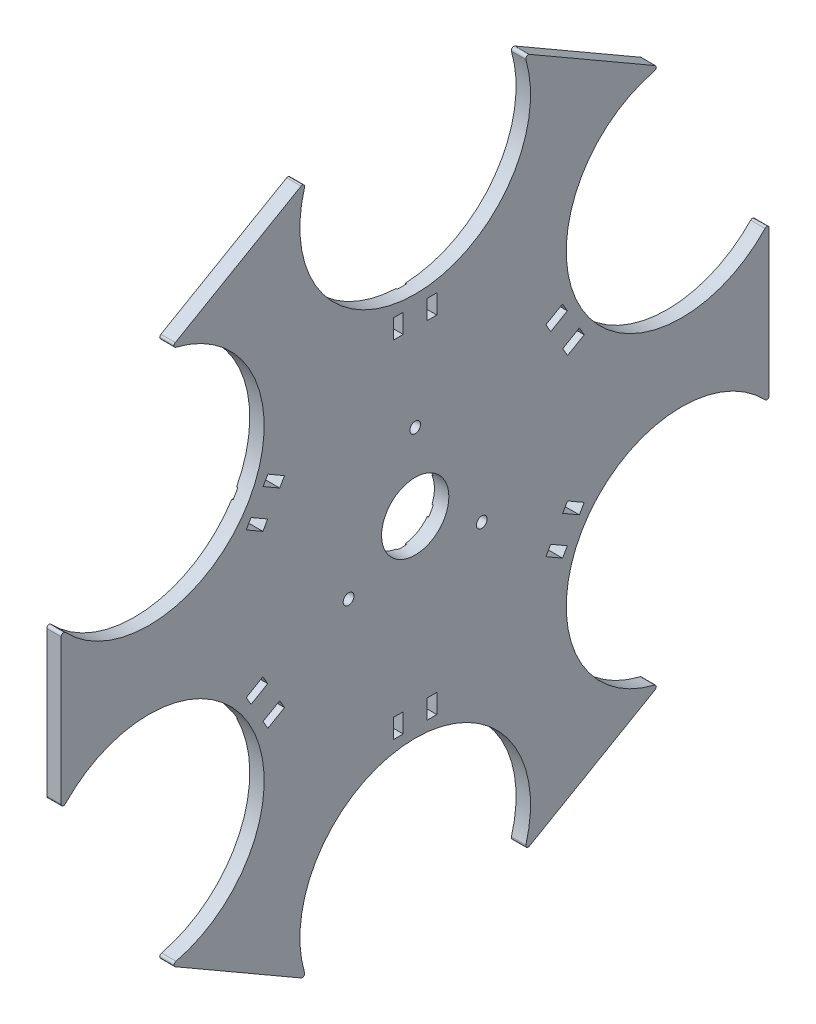
SolidWorks part; units mm, degrees
ref_plane "Front Plane" through (0, 0, 0) normal (0, 0, 1) x (1, 0, 0)
ref_plane "Top Plane" through (0, 0, 0) normal (0, 1, 0) x (1, 0, 0)
ref_plane "Right Plane" through (0, 0, 0) normal (1, 0, 0) x (0, 0, -1)
sketch "Sketch2" plane through (0, 0, 0) normal (1, 0, 0) x (0, 0, -1)
  line L0 (35.921, 114.3) -> (-35.921, 114.3) construction
  line L1 (81.0262, 88.2585) -> (35.921, 114.3)
  line L2 (116.9472, -26.0415) -> (116.9472, 26.0415)
  line L3 (35.921, -114.3) -> (81.0262, -88.2585)
  line L4 (-81.0262, -88.2585) -> (-35.921, -114.3)
  line L5 (-116.9472, 26.0415) -> (-116.9472, -26.0415)
  line L6 (-35.921, 114.3) -> (-81.0262, 88.2585)
  circle A0 centre (0, 0) radius 101.6 construction
  arc A1 (-35.921, 114.3) -> (35.921, 114.3) centre (0, 101.6) ccw
  arc A2 (81.0262, 88.2585) -> (116.9472, 26.0415) centre (87.9882, 50.8) ccw
  arc A3 (116.9472, -26.0415) -> (81.0262, -88.2585) centre (87.9882, -50.8) ccw
  arc A4 (35.921, -114.3) -> (-35.921, -114.3) centre (0, -101.6) ccw
  arc A5 (-81.0262, -88.2585) -> (-116.9472, -26.0415) centre (-87.9882, -50.8) ccw
  arc A6 (-116.9472, 26.0415) -> (-81.0262, 88.2585) centre (-87.9882, 50.8) ccw
  circle A7 centre (0, 0) radius 11.11
  point P23 (0, 0)
  point P34 (0, 0)
  dimension "D1" = 203.2
  dimension "D2" = 114.3
  dimension "D3" = 76.2
  dimension "D4" = 6
  dimension "D5" = 6
extrude "Boss-Extrude1" add sketch "Sketch2" along normal blind 4.7625
sketch "Sketch3" plane through (0, 0, 0) normal (-1, 0, 0) x (0, 0, 1)
  line L0 (1.5875, 10.6044) -> (-1.5875, 10.6044)
  line L1 (1.5875, 192.5956) -> (-1.5875, 192.5956)
  line L2 (1.5875, 192.5956) -> (1.5875, 10.6044)
  line L3 (167.5864, 94.923) -> (165.9989, 97.6726)
  line L4 (-1.5875, 192.5956) -> (-1.5875, 10.6044)
  line L5 (1.5875, 192.5956) -> (-1.5875, 10.6044) construction
  line L6 (1.5875, 10.6044) -> (-1.5875, 192.5956) construction
  line L7 (167.5864, 94.923) -> (9.9774, 3.9274)
  line L8 (165.9989, 97.6726) -> (8.3899, 6.677)
  line L9 (9.9774, 3.9274) -> (8.3899, 6.677)
  line L10 (165.9989, -97.6726) -> (167.5864, -94.923)
  line L11 (165.9989, -97.6726) -> (8.3899, -6.677)
  line L12 (167.5864, -94.923) -> (9.9774, -3.9274)
  line L13 (8.3899, -6.677) -> (9.9774, -3.9274)
  line L14 (-1.5875, -192.5956) -> (1.5875, -192.5956)
  line L15 (-1.5875, -192.5956) -> (-1.5875, -10.6044)
  line L16 (1.5875, -192.5956) -> (1.5875, -10.6044)
  line L17 (-1.5875, -10.6044) -> (1.5875, -10.6044)
  line L18 (-167.5864, -94.923) -> (-165.9989, -97.6726)
  line L19 (-167.5864, -94.923) -> (-9.9774, -3.9274)
  line L20 (-165.9989, -97.6726) -> (-8.3899, -6.677)
  line L21 (-9.9774, -3.9274) -> (-8.3899, -6.677)
  line L22 (-165.9989, 97.6726) -> (-167.5864, 94.923)
  line L23 (-165.9989, 97.6726) -> (-8.3899, 6.677)
  line L24 (-167.5864, 94.923) -> (-9.9774, 3.9274)
  line L25 (-8.3899, 6.677) -> (-9.9774, 3.9274)
  point P0 (0, 101.6)
  point P28 (0, 0)
  point P29 (0, 0)
  dimension "D1" = 3.175
  dimension "D2" = 6
extrude "Cut-Extrude1" cut sketch "Sketch3" against normal blind 0.3969
fillet "Fillet1" radius 0.7937 12 edges at (2.3813, -114.3, 35.921) (2.3813, -114.3, -35.921) (2.3813, -88.2585, -81.0262) (2.3813, -26.0415, -116.9472) (2.3813, 88.2585, -81.0262) (2.3813, 26.0415, -116.9472) (2.3813, -88.2585, 81.0262) (2.3813, -26.0415, 116.9472) (2.3813, 26.0415, 116.9472) (2.3813, 88.2585, 81.0262) (2.3813, 114.3, -35.921) (2.3813, 114.3, 35.921)
hole_wizard "9/64 (0.14063) Diameter Hole1" positions "Sketch7" profile "Sketch6" hole size "9/64" standard "ANSI Inch" end condition through all
sketch "Sketch7" plane through (0, 0, 0) normal (-1, 0, 0) x (0, 0, 1)
  line L0 (0, 0) -> (0, 25.4) construction
  line L1 (0, 0) -> (21.997, -12.7) construction
  line L2 (0, 0) -> (-21.997, -12.7) construction
  circle A0 centre (0, 0) radius 25.4
  point P5 (0, 25.4)
  point P10 (21.997, -12.7)
  point P13 (-21.997, -12.7)
  dimension "D1" = 120
  dimension "D2" = 120
sketch "Sketch6" plane through (0, 25.4, 0) normal (0, 1, 0) x (0, 0, 1)
  line L0 (0, 0) -> (0, 4.7625)
  line L1 (0, 4.7625) -> (1.786, 4.7625)
  line L2 (1.786, 4.7625) -> (1.786, 0)
  line L5 (1.786, 0) -> (0, 0)
  line L11 (0, -6.35) -> (0, 107.95) construction
  dimension "Thru Hole Dia." = 3.572
  dimension "Thru Hole Depth" = 4.7625
sketch "Sketch8" plane through (0, 0, 0) normal (-1, 0, 0) x (0, 0, 1)
  line L0 (0, 63.5) -> (0, 43.4086) construction
  line L1 (3.9687, 60.325) -> (3.9687, 53.975)
  line L2 (-3.9687, 60.325) -> (-7.1437, 60.325)
  line L3 (-3.9687, 60.325) -> (-3.9687, 53.975)
  line L4 (-3.9687, 53.975) -> (-7.1437, 53.975)
  line L5 (-7.1437, 60.325) -> (-7.1437, 53.975)
  line L6 (3.9687, 60.325) -> (7.1437, 60.325)
  line L7 (7.1437, 60.325) -> (7.1437, 53.975)
  line L8 (3.9687, 53.975) -> (7.1437, 53.975)
  line L9 (44.7593, 30.4245) -> (43.1718, 33.1742)
  line L10 (50.2586, 33.5995) -> (44.7593, 30.4245)
  line L11 (48.6711, 36.3492) -> (43.1718, 33.1742)
  line L12 (50.2586, 33.5995) -> (48.6711, 36.3492)
  line L13 (54.2274, 26.7255) -> (55.8149, 23.9758)
  line L14 (48.7281, 23.5505) -> (50.3156, 20.8008)
  line L15 (54.2274, 26.7255) -> (48.7281, 23.5505)
  line L16 (55.8149, 23.9758) -> (50.3156, 20.8008)
  line L17 (48.7281, -23.5505) -> (50.3156, -20.8008)
  line L18 (54.2274, -26.7255) -> (48.7281, -23.5505)
  line L19 (55.8149, -23.9758) -> (50.3156, -20.8008)
  line L20 (54.2274, -26.7255) -> (55.8149, -23.9758)
  line L21 (50.2586, -33.5995) -> (48.6711, -36.3492)
  line L22 (44.7593, -30.4245) -> (43.1718, -33.1742)
  line L23 (50.2586, -33.5995) -> (44.7593, -30.4245)
  line L24 (48.6711, -36.3492) -> (43.1718, -33.1742)
  line L25 (3.9688, -53.975) -> (7.1438, -53.975)
  line L26 (3.9688, -60.325) -> (3.9688, -53.975)
  line L27 (7.1438, -60.325) -> (7.1438, -53.975)
  line L28 (3.9688, -60.325) -> (7.1438, -60.325)
  line L29 (-3.9687, -60.325) -> (-7.1437, -60.325)
  line L30 (-3.9687, -53.975) -> (-7.1437, -53.975)
  line L31 (-3.9687, -60.325) -> (-3.9687, -53.975)
  line L32 (-7.1437, -60.325) -> (-7.1437, -53.975)
  line L33 (-44.7593, -30.4245) -> (-43.1718, -33.1742)
  line L34 (-50.2586, -33.5995) -> (-44.7593, -30.4245)
  line L35 (-48.6711, -36.3492) -> (-43.1718, -33.1742)
  line L36 (-50.2586, -33.5995) -> (-48.6711, -36.3492)
  line L37 (-54.2274, -26.7255) -> (-55.8149, -23.9758)
  line L38 (-48.7281, -23.5505) -> (-50.3156, -20.8008)
  line L39 (-54.2274, -26.7255) -> (-48.7281, -23.5505)
  line L40 (-55.8149, -23.9758) -> (-50.3156, -20.8008)
  line L41 (-48.7281, 23.5505) -> (-50.3156, 20.8008)
  line L42 (-54.2274, 26.7255) -> (-48.7281, 23.5505)
  line L43 (-55.8149, 23.9758) -> (-50.3156, 20.8008)
  line L44 (-54.2274, 26.7255) -> (-55.8149, 23.9758)
  line L45 (-50.2586, 33.5995) -> (-48.6711, 36.3492)
  line L46 (-44.7593, 30.4245) -> (-43.1718, 33.1742)
  line L47 (-50.2586, 33.5995) -> (-44.7593, 30.4245)
  line L48 (-48.6711, 36.3492) -> (-43.1718, 33.1742)
  arc A0 (-1.5875, 63.5331) -> (1.5875, 63.5331) centre (0, 101.6) ccw construction
  point P57 (0, 0)
  dimension "D1" = 3.175
  dimension "D2" = 6.35
  dimension "D3" = 3.9688
  dimension "D4" = 3.175
  dimension "D5" = 6
extrude "Cut-Extrude2" cut sketch "Sketch8" against normal through all
